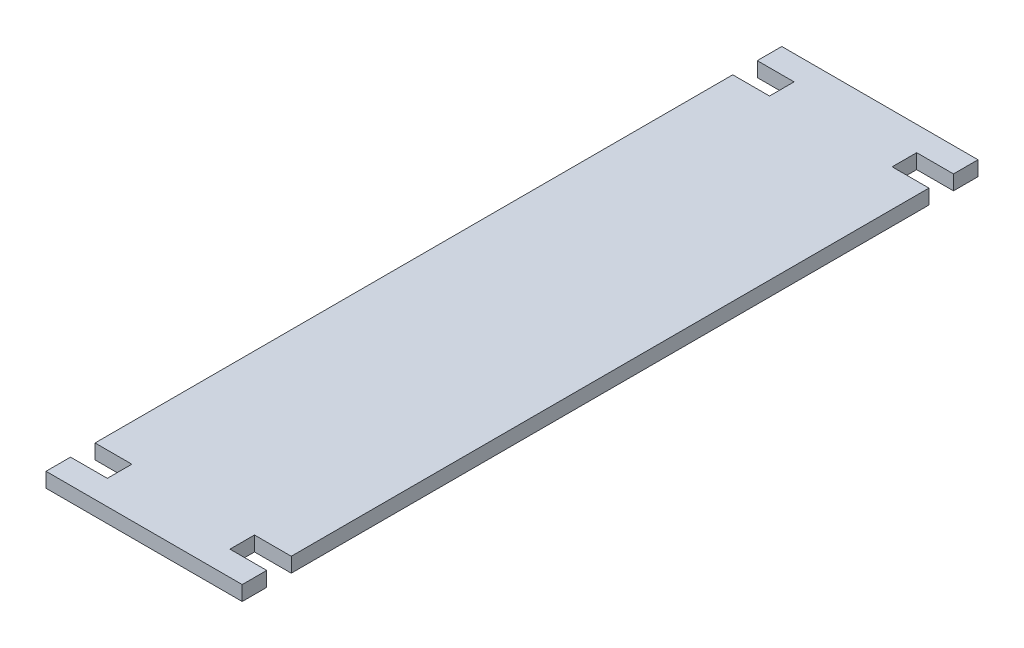
SolidWorks part; units mm, degrees
ref_plane "Front Plane" through (0, 0, 0) normal (0, 0, 1) x (1, 0, 0)
ref_plane "Top Plane" through (0, 0, 0) normal (0, 1, 0) x (1, 0, 0)
ref_plane "Right Plane" through (0, 0, 0) normal (1, 0, 0) x (0, 0, -1)
sketch "Sketch1" plane through (0, 0, 0) normal (0, 1, 0) x (1, 0, 0)
  line L1 (0, 0) -> (40, 0)
  line L2 (0, 0) -> (0, 150)
  line L3 (0, 150) -> (40, 150)
  line L4 (40, 0) -> (40, 150)
  dimension "D1" = 40
  dimension "D2" = 150
extrude "Boss-Extrude1" add sketch "Sketch1" along normal blind 3
sketch "Sketch2" plane through (0, 0, 0) normal (0, 1, 0) x (1, 0, 0)
  line L0 (0, 145) -> (7.5, 145)
  line L1 (0, 150) -> (0, 0) construction
  line L2 (7.5, 145) -> (7.5, 140)
  line L3 (7.5, 140) -> (0, 140)
  line L4 (0, 145) -> (0, 140)
  line L5 (20, 150) -> (20, 0)
  line L6 (40, 150) -> (0, 150) construction
  line L7 (0, 0) -> (40, 0) construction
  line L8 (0, 75) -> (40, 75)
  line L9 (40, 0) -> (40, 150) construction
  line L10 (40, 145) -> (40, 140)
  line L11 (32.5, 145) -> (32.5, 140)
  line L12 (40, 145) -> (32.5, 145)
  line L13 (32.5, 140) -> (40, 140)
  line L14 (32.5, 10) -> (40, 10)
  line L15 (40, 5) -> (32.5, 5)
  line L16 (32.5, 5) -> (32.5, 10)
  line L17 (40, 5) -> (40, 10)
  line L18 (0, 5) -> (0, 10)
  line L19 (7.5, 10) -> (0, 10)
  line L20 (7.5, 5) -> (7.5, 10)
  line L21 (0, 5) -> (7.5, 5)
  dimension "D1" = 7.5
  dimension "D2" = 5
  dimension "D3" = 5
extrude "Cut-Extrude1" cut sketch "Sketch2" along normal blind 10 contours L0 L4 L3 L2 | L15 L17 L14 L16 | L18 L21 L20 L19 | L11 L13 L10 L12
